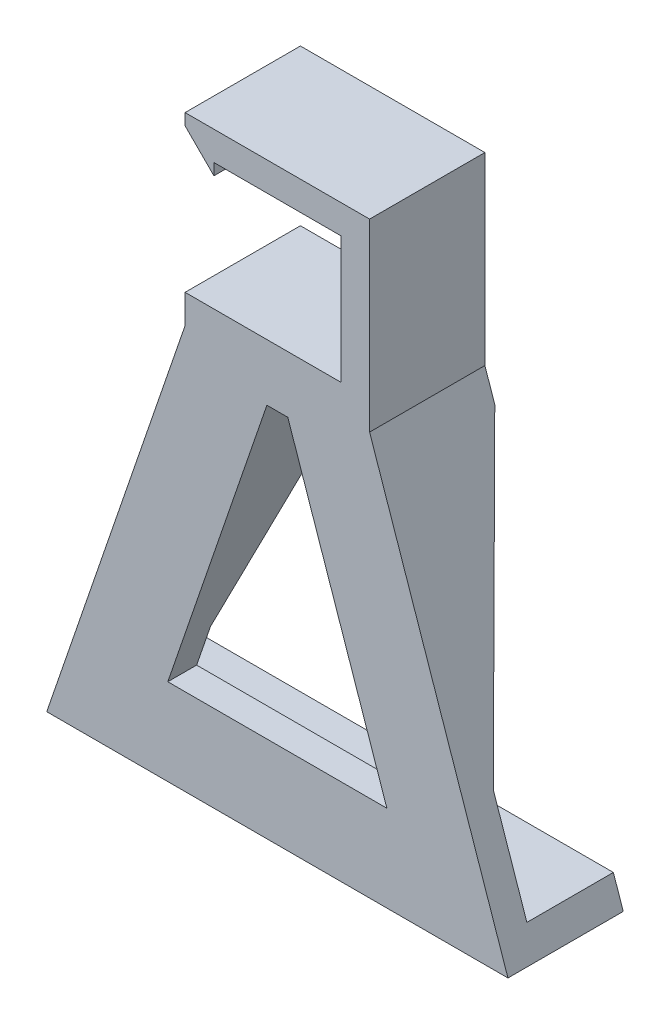
SolidWorks part; units mm, degrees
ref_plane "Front Plane" through (0, 0, 0) normal (0, 0, 1) x (1, 0, 0)
ref_plane "Top Plane" through (0, 0, 0) normal (0, 1, 0) x (1, 0, 0)
ref_plane "Right Plane" through (0, 0, 0) normal (1, 0, 0) x (0, 0, -1)
sketch "Sketch2" plane through (0, 0, 0) normal (0, 0, 1) x (1, 0, 0)
  line L0 (16, 16) -> (16, -16)
  line L1 (-11, 11) -> (11, 11)
  line L2 (-11, 11) -> (-11, 9)
  line L3 (-11, -11) -> (11, -11)
  line L4 (11, 11) -> (11, -11)
  line L5 (-11, 11) -> (11, -11) construction
  line L6 (-11, -11) -> (11, 11) construction
  line L7 (-16, -16) -> (16, -16)
  line L8 (-16, 16) -> (-16, 14)
  line L9 (-16, 16) -> (16, 16)
  line L10 (-11, 9) -> (-16, 14)
  line L11 (-11, -11) -> (-16, -11)
  line L12 (-16, -11) -> (-16, -16)
  line L13 (-16, 16) -> (-16, -16) construction
  line L14 (-11, 11) -> (-11, -11) construction
  point P0 (0, 0)
  point P12 (-11, -11)
  dimension "D1" = 22
  dimension "D2" = 22
  dimension "D4" = 2
  dimension "D5" = 45
  dimension "D3" = 5
extrude "Boss-Extrude1" add sketch "Sketch2" along normal blind 20
ref_plane "Plane1" through (0, -86, 0) normal (0, -1, 0) x (-1, 0, 0)
sketch "Sketch3" plane through (0, -16, 0) normal (0, -1, 0) x (1, 0, 0)
  line L9 (-16, 0) -> (16, 0)
  line L10 (16, 0) -> (16, 20)
  line L11 (16, 20) -> (-16, 20)
  line L12 (-16, 20) -> (-16, 0)
  line L13 (-16, 0) -> (16, 0)
  line L14 (16, 0) -> (16, 20)
  line L15 (16, 20) -> (-16, 20)
  line L16 (-16, 20) -> (-16, 0)
  point P2 (0, 0)
  point P5 (16, 20)
  dimension "D1" = 0
sketch "Sketch4" plane through (0, -86, 0) normal (0, -1, 0) x (-1, 0, 0)
  line L1 (40, 0) -> (-40, 0)
  line L2 (40, 0) -> (40, -20)
  line L3 (40, -20) -> (-40, -20)
  line L4 (-40, 0) -> (-40, -20)
  point P4 (0, 0)
  dimension "D1" = 80
loft "Loft1" add profiles "Sketch3", "Sketch4"
sketch "Sketch5" plane through (0, 0, 0) normal (1, 0, 0) x (0, 0, -1)
  line L0 (0, -81) -> (-15, -81)
  line L1 (0, -16) -> (0, -86) construction
  line L2 (-15, -81) -> (-15, -64)
  line L3 (-15, -64) -> (0, -21)
  line L4 (0, -21) -> (0, -81)
  line L5 (0, -86) -> (-20, -86) construction
  line L6 (-20, -16) -> (-20, -86) construction
  line L7 (-20, -16) -> (0, -16) construction
  point P4 (0.6467, -72.629)
  dimension "D1" = 5
  dimension "D2" = 5
  dimension "D3" = 17
  dimension "D4" = 5
extrude "Cut-Extrude1" cut sketch "Sketch5" against normal through all both and the other way through all
sketch "Sketch6" plane through (0, 0, 0) normal (0, 0, 1) x (1, 0, 0)
  line L6 (-1.8108, -20.8649) -> (1.8108, -20.8649)
  line L9 (-19, -71) -> (-1.8108, -20.8649)
  line L10 (19, -71) -> (-19, -71)
  line L11 (1.8108, -20.8649) -> (19, -71)
  line L12 (-19, -71) -> (-1.8108, -20.8649)
  line L13 (19, -71) -> (-19, -71)
  line L14 (1.8108, -20.8649) -> (19, -71)
  dimension "D1" = 15
extrude "Cut-Extrude3" cut sketch "Sketch6" along normal through all
